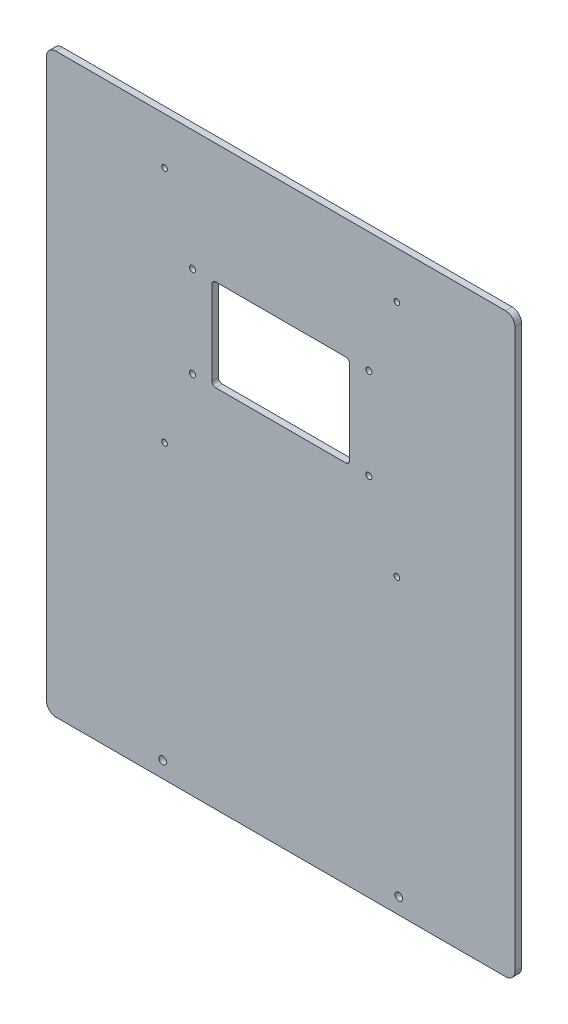
SolidWorks part; units mm, degrees
ref_plane "Plan de face" through (0, 0, 0) normal (0, 0, 1) x (1, 0, 0)
ref_plane "Plan de dessus" through (0, 0, 0) normal (0, 1, 0) x (1, 0, 0)
ref_plane "Plan de droite" through (0, 0, 0) normal (1, 0, 0) x (0, 0, -1)
sketch "Esquisse1" plane through (0, 0, 0) normal (0, 0, 1) x (1, 0, 0)
  line L1 (5, 0) -> (245, 0)
  line L2 (0, 5) -> (0, 302.81)
  line L3 (5, 307.81) -> (245, 307.81)
  line L4 (250, 5) -> (250, 302.81)
  arc A0 (250, 5) -> (245, 0) centre (245, 5) cw
  arc A1 (250, 302.81) -> (245, 307.81) centre (245, 302.81) ccw
  arc A2 (5, 0) -> (0, 5) centre (5, 5) cw
  arc A3 (5, 307.81) -> (0, 302.81) centre (5, 302.81) ccw
  point P9 (250, 307.81)
  point P12 (0, 0)
  point P15 (0, 307.81)
  dimension "D3" = 5
  dimension "D1" = 250
  dimension "D2" = 307.81
extrude "Boss.-Extru.1" add sketch "Esquisse1" along normal blind 3.5
sketch "Esquisse2" plane through (0, 0, 3.5) normal (0, 0, 1) x (1, 0, 0)
  line L0 (-35.7922, 8.5) -> (305.0105, 8.5) construction
  line L1 (5, 0) -> (245, 0) construction
  line L2 (0, 302.81) -> (0, 5) construction
  circle A0 centre (62, 8.5) radius 2
  circle A1 centre (188, 8.5) radius 2
  dimension "D2" = 4
  dimension "D5" = 4
  dimension "D1" = 8.5
  dimension "D3" = 62
  dimension "D4" = 126
extrude "Enlèv. mat.-Extru.1" cut sketch "Esquisse2" against normal through all
sketch "Esquisse3" plane through (0, 0, 3.5) normal (0, 0, 1) x (1, 0, 0)
  line L0 (125, 563.6946) -> (125, 51.9254) construction
  line L1 (245, 307.81) -> (5, 307.81) construction
  line L2 (21.2655, 219.31) -> (234.7147, 219.31) construction
  circle A0 centre (63, 155.81) radius 1.5
  circle A1 centre (63, 282.81) radius 1.5
  circle A2 centre (187, 282.81) radius 1.5
  circle A3 centre (187, 155.81) radius 1.5
  circle A4 centre (77.95, 243.58) radius 1.6
  circle A5 centre (172.05, 243.58) radius 1.6
  circle A6 centre (77.95, 195.04) radius 1.6
  circle A7 centre (172.05, 195.04) radius 1.6
  point P4 (125, 307.81)
  dimension "D3" = 3
  dimension "D4" = 3
  dimension "D5" = 3
  dimension "D6" = 3
  dimension "D17" = 3.2
  dimension "D18" = 3.2
  dimension "D19" = 3.2
  dimension "D20" = 3.2
  dimension "D15" = 24.27
  dimension "D1" = 124
  dimension "D2" = 124
  dimension "D7" = 127
  dimension "D8" = 127
  dimension "D9" = 25
  dimension "D10" = 62
  dimension "D11" = 94.1
  dimension "D12" = 47.05
  dimension "D13" = 48.54
  dimension "D14" = 48.54
  dimension "D16" = 47.05
  dimension "D21" = 24.27
  dimension "D22" = 63.5
  dimension "D23" = 25
extrude "Enlèv. mat.-Extru.2" cut sketch "Esquisse3" against normal through all
sketch "Esquisse4" plane through (0, 0, 3.5) normal (0, 0, 1) x (1, 0, 0)
  line L0 (125, 307.81) -> (125, 35.1539) construction
  line L1 (90.28, 243.79) -> (159.72, 243.79)
  line L2 (88.28, 241.79) -> (88.28, 196.83)
  line L3 (90.28, 194.83) -> (159.72, 194.83)
  line L4 (161.72, 241.79) -> (161.72, 196.83)
  line L5 (245, 307.81) -> (5, 307.81) construction
  line L6 (47.2411, 219.31) -> (206.1568, 219.31) construction
  circle A1 centre (77.95, 243.58) radius 1.6 construction
  arc A2 (159.72, 243.79) -> (161.72, 241.79) centre (159.72, 241.79) cw
  arc A3 (161.72, 196.83) -> (159.72, 194.83) centre (159.72, 196.83) cw
  arc A4 (90.28, 194.83) -> (88.28, 196.83) centre (90.28, 196.83) cw
  arc A5 (90.28, 243.79) -> (88.28, 241.79) centre (90.28, 241.79) ccw
  point P4 (125, 243.79)
  point P13 (88.28, 219.31)
  point P16 (161.72, 243.79)
  point P21 (88.28, 194.83)
  point P24 (88.28, 243.79)
  dimension "D3" = 24.27
  dimension "D4" = 2
  dimension "D1" = 73.44
  dimension "D2" = 48.96
extrude "Enlèv. mat.-Extru.3" cut sketch "Esquisse4" against normal through all
